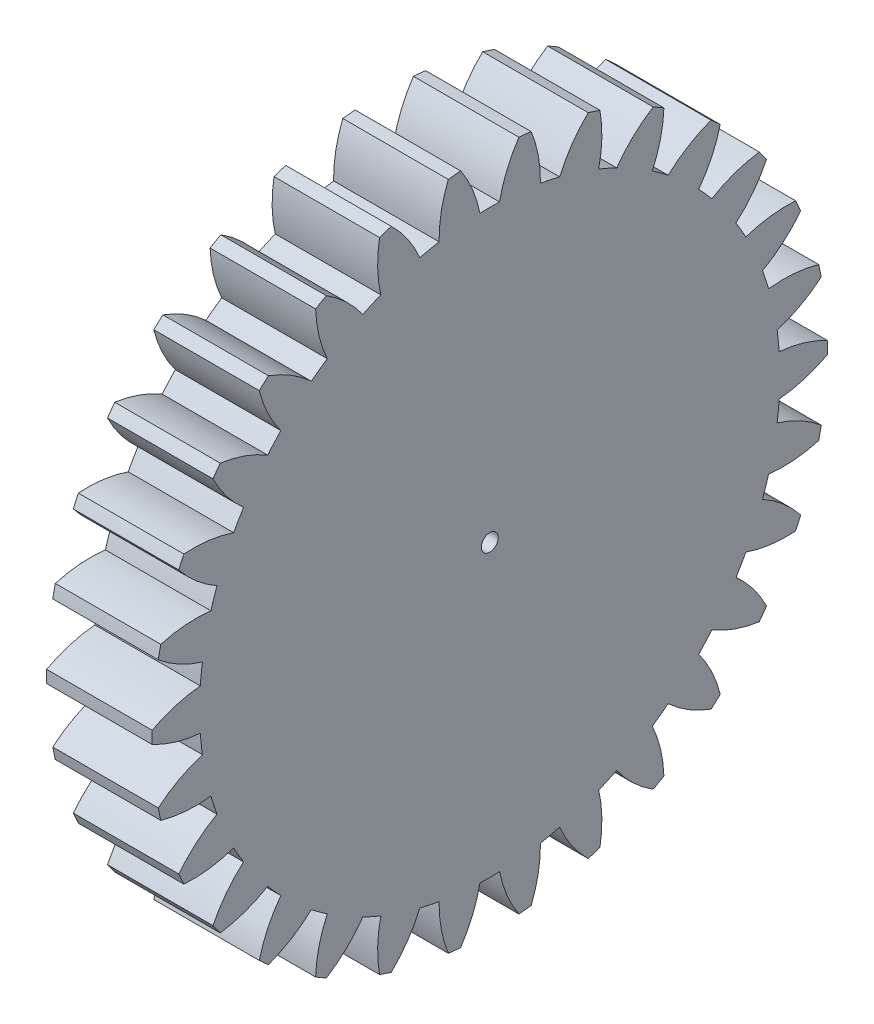
SolidWorks part; units mm, degrees
ref_plane "Plane1" through (0, 0, 0) normal (0, 0, 1) x (1, 0, 0)
ref_plane "Plane2" through (0, 0, 0) normal (0, 1, 0) x (1, 0, 0)
ref_plane "Plane3" through (0, 0, 0) normal (1, 0, 0) x (0, 0, -1)
other "Configuration Table"
sketch "HoldingSke" plane through (0, 0, 0) normal (0, 1, 0) x (1, 0, 0)
  line L0 (0, 0) -> (0.866, -0.5)
  line L1 (-15, 0) -> (100, 0) construction
  line L2 (0, 0) -> (-2.1039, 2.3779)
  line L3 (0, 0) -> (-11.863, 4.5341)
  line L4 (0, 0) -> (7.479, 4.318)
  line L5 (0, 0) -> (-46.8476, -17.4728)
  line L6 (0, 0) -> (-4.1448, -2.7965)
  line L7 (-2.1039, 2.3779) -> (8.6586, 51.2059)
  line L8 (-76.2, 54.61) -> (-76.1, 54.61)
  line L9 (-71.009, 38.7566) -> (-53.1078, 45.2721)
  line L10 (-76.2, 71.12) -> (104.1128, 71.12)
  line L11 (0, 0) -> (-5, 0)
  line L12 (-76.2, 101.6) -> (-76.162, 101.6)
  line L13 (24.9733, 27.94) -> (52.9518, 28.4284)
  line L14 (24.9733, 27.94) -> (24.9743, 27.94)
  line L15 (24.9733, 27.94) -> (100.4006, 29.5858)
  line L16 (-63.627, -1) -> (-12.827, -1)
  circle A0 centre (0, 0) radius 0.4
  circle A1 centre (0, 0) radius 13.749
  circle A2 centre (0, 0) radius 37.5
  circle A3 centre (0, 0) radius 0.4
  dimension "MHD" = 27.498
  dimension "Hub_dia" = 75
  dimension "Bore" = 0.8
  dimension "MBD" = 0.8
  dimension "Num_teeth" = 30
  dimension "Pitch" = 1
  dimension "Overall_len" = 50
  dimension "Show_teeth" = 30
  dimension "Thickness" = 5
  dimension "OAL" = 50.0001
  dimension "T_dim" = 0.1
  dimension "Ap" = 20
  dimension "H" = 19.05
  dimension "Pitch_radius" = 180.3128
  dimension "Width" = 5
  dimension "Backlash" = 0.038
  dimension "Addendum_fac" = 1
  dimension "Dedendum_fac" = 1.25
  dimension "Clearance_fac" = 0.25
  dimension "Dedendum_add" = 0.001
  dimension "Module" = 1
sketch "BasProSke" plane through (0, 0, 0) normal (0, 1, 0) x (1, 0, 0)
  line L0 (-10, 0) -> (60, 0) construction
  line L1 (0, 0) -> (0, 16)
  line L2 (0, 0) -> (5, 0)
  line L3 (5, 0) -> (5, 16)
  line L4 (5, 16) -> (0, 16)
  dimension "Thickness" = 5
  dimension "Diameter" = 32
revolve "Base-Revolve" add sketch "BasProSke" angle 360 about L0
sketch "TooCutSke" plane through (0, 0, 0) normal (1, 0, 0) x (0, 0, -1)
  line L1 (0, 0) -> (0, 107) construction
  line L2 (0, 0) -> (-0.8515, 14.9758) construction
  line L3 (0, 0) -> (-3.1323, 29.8014) construction
  line L4 (-0.8515, 14.9758) -> (-1.5661, 14.9007) construction
  arc A0 (0.4664, 13.7411) -> (-0.4664, 13.7411) centre (0, 0) ccw
  arc A1 (1.3975, 15.9644) -> (-1.3975, 15.9644) centre (0, 0) ccw
  circle A2 centre (0, 0) radius 15 construction
  circle A3 centre (0, 0) radius 14.0954 construction
  arc A4 (-0.4664, 13.7411) -> (-1.3975, 15.9644) centre (-6.3534, 12.5823) ccw
  arc A5 (1.3975, 15.9644) -> (0.4664, 13.7411) centre (6.3534, 12.5823) ccw
  dimension "Root_dia" = 27.498
  dimension "Overcut_dia" = 32.0508
  dimension "Pitch_dia" = 30
  dimension "Base_dia" = 28.1908
  dimension "Flank_rad" = 6
  dimension "Half_ang" = 6
  dimension "Half_CT" = 0.7185
extrude "ToothCut" cut sketch "TooCutSke" along normal through all
fillet "Breaks" [suppressed] radius 0.02
fillet "RootFillets" [suppressed] radius 0.251
pattern_circular "TeethCuts" count 30 every 12 about axis through (-10, 0, 0) along (1, 0, 0) of "ToothCut", "RootFillets", "Breaks"
sketch "HubNeaOneSke" plane through (0, 0, 0) normal (-1, 0, 0) x (0, 0, 1)
  circle A0 centre (0, 0) radius 13.749
  dimension "Diameter" = 27.498
extrude "HubNearOne" [suppressed] add sketch "HubNeaOneSke" along normal blind 45.0001
sketch "HubNeaBotSke" plane through (0, 0, 0) normal (-1, 0, 0) x (0, 0, 1)
  circle A0 centre (0, 0) radius 13.749
  dimension "Diameter" = 27.498
extrude "HubNearBoth" [suppressed] add sketch "HubNeaBotSke" along normal blind 22.5
ref_plane "FarPln" through (5, 0, 0) normal (1, 0, 0) x (0, 0, -1)
sketch "HubFarSke" plane through (5, 0, 0) normal (1, 0, 0) x (0, 0, -1)
  circle A0 centre (0, 0) radius 13.749
  dimension "Diameter" = 27.498
extrude "HubFar" [suppressed] add sketch "HubFarSke" along normal blind 22.5
sketch "BorSke" plane through (0, 0, 0) normal (1, 0, 0) x (0, 0, -1)
  circle A0 centre (0, 0) radius 0.4
  dimension "Diameter" = 0.8
extrude "Bore" cut sketch "BorSke" along normal mid plane 100.0001
sketch "KeySke" plane through (0, 0, 0) normal (1, 0, 0) x (0, 0, -1)
  line L0 (-0.05, 0) -> (-0.05, 0.5)
  line L1 (-0.05, 0.5) -> (0.05, 0.5)
  line L2 (0.05, 0.5) -> (0.05, 0)
  line L3 (0, 0) -> (0, 34) construction
  line L4 (-0.05, 0) -> (0.05, 0)
  dimension "Offset" = 0.5
  dimension "Width" = 0.1
extrude "Keyway" [suppressed] cut sketch "KeySke" along normal mid plane 100.0001
pattern_circular "Keyway2" [suppressed] count 2 every 90 about axis through (-10, 0, 0) along (1, 0, 0)
equation "' \"Module@HoldingSke\" = 6.35"
equation "' \"Num_teeth@HoldingSke\" = 12"
equation "' \"Ap@HoldingSke\" =  20"
equation "' \"Ap@HoldingSke\" = 20"
equation "' \"Width@HoldingSke\" = 0.5 * 25.4"
equation "' \"Hub_dia@HoldingSke\"= 1 * 25.4"
equation "' \"Hub_dia@HoldingSke\" = 1 * 25.4"
equation "' \"Overall_len@HoldingSke\" = 1.0 * 25.4"
equation "' \"Bore@HoldingSke\" = 0.75 * 25.4"
equation "' \"T_dim@HoldingSke\" = 0.1 * 25.4"
equation "' \"Width@KeySke\" = 0.25 * 25.4"
equation "' \"Show_teeth@HoldingSke\" = 13"
equation "' \"Backlash@HoldingSke\" = 0.009 * 25.4"
equation "' \"Addendum_fac@HoldingSke\" = 1.0"
equation "' \"Dedendum_fac@HoldingSke\" = 1.25"
equation "' \"Dedendum_add@HoldingSke\" = 0.00005 * 25.4"
equation "' \"Clearance_fac@HoldingSke\" = 0.25"
equation "\"Pitch@HoldingSke\" = 1 / \"Module@HoldingSke\""
equation "\"Overcut_dia@TooCutSke\" = (\"Num_teeth@HoldingSke\" + 2 * \"Addendum_fac@HoldingSke\") / \"Pitch@HoldingSke\" + 0.002 * 25.4"
equation "\"Pitch_dia@TooCutSke\" = \"Num_teeth@HoldingSke\" / \"Pitch@HoldingSke\""
equation "\"Base_dia@TooCutSke\" = \"Num_teeth@HoldingSke\" / \"Pitch@HoldingSke\" * cos((\"Ap@HoldingSke\"  * 3.14159265 / 180))"
equation "\"Root_dia@TooCutSke\" = (\"Num_teeth@HoldingSke\" + 2) / \"Pitch@HoldingSke\" - 2 * (\"Addendum_fac@HoldingSke\" + \"Dedendum_fac@HoldingSke\") / \"Pitch@HoldingSke\" - \"Dedendum_add@HoldingSke\" * 2"
equation "\"Half_ang@TooCutSke\" = 180 / \"Num_teeth@HoldingSke\""
equation "\"Half_CT@TooCutSke\" = \"Num_teeth@HoldingSke\" / \"Pitch@HoldingSke\" * sin((3.14159265 / 2 / \"Num_teeth@HoldingSke\")) / 2 - 7 * \"Backlash@HoldingSke\" / 4"
equation "\"Flank_rad@TooCutSke\" = \"Num_teeth@HoldingSke\" / \"Pitch@HoldingSke\" / 5"
equation "\"Radius@RootFillets\" = \"Clearance_fac@HoldingSke\" / \"Pitch@HoldingSke\" + \"Dedendum_add@HoldingSke\""
equation "\"Break_rad@Breaks\" = 0.02 / \"Pitch@HoldingSke\""
equation "\"Thickness@HoldingSke\" = \"Width@HoldingSke\""
equation "\"OAL@HoldingSke\" = \"Thickness@HoldingSke\""
equation "\"MHD@HoldingSke\" = (\"Num_teeth@HoldingSke\" + 2) / \"Pitch@HoldingSke\" - 2 * (\"Addendum_fac@HoldingSke\" + \"Dedendum_fac@HoldingSke\")  / \"Pitch@HoldingSke\" - \"Dedendum_add@HoldingSke\" * 2"
equation "\"MBD@HoldingSke\" = (\"Num_teeth@HoldingSke\" + 2) / \"Pitch@HoldingSke\" - 2 * (\"Addendum_fac@HoldingSke\" + \"Dedendum_fac@HoldingSke\")  / \"Pitch@HoldingSke\" - \"Dedendum_add@HoldingSke\" * 2 - 0.002 * 25.4"
equation "\"MHD@HoldingSke\" = ((sgn( \"MHD@HoldingSke\" - \"Hub_dia@HoldingSke\" )-1)*( \"MHD@HoldingSke\" - \"Hub_dia@HoldingSke\" ))/-2+ \"Hub_dia@HoldingSke\""
equation "\"MBD@HoldingSke\" = ((sgn( \"MBD@HoldingSke\" - \"Bore@HoldingSke\" )-1)*( \"MBD@HoldingSke\" - \"Bore@HoldingSke\" ))/-2+ \"Bore@HoldingSke\""
equation "\"OAL@HoldingSke\" = ((sgn( \"OAL@HoldingSke\" - \"Overall_len@HoldingSke\" )+1)*( \"OAL@HoldingSke\" - \"Overall_len@HoldingSke\" ))/2 + \"Overall_len@HoldingSke\" + 0.000002 * 25.4"
equation "\"Num_teeth@TeethCuts\" = int( \"Show_teeth@HoldingSke\" ) + 1"
equation "\"Num_teeth@TeethCuts\" = ((sgn( \"Num_teeth@TeethCuts\" - \"Num_teeth@HoldingSke\" )-1)*( \"Num_teeth@TeethCuts\" - \"Num_teeth@HoldingSke\" ))/-2+ \"Num_teeth@HoldingSke\""
equation "\"Num_teeth@TeethCuts\" = ((sgn( \"Num_teeth@TeethCuts\" - 2.0)+1)*( \"Num_teeth@TeethCuts\" - 2.0))/2 +2.0"
equation "\"Angle@TeethCuts\" = 360.0 / \"Num_teeth@HoldingSke\""
equation "\"Diameter@BasProSke\" = (\"Num_teeth@HoldingSke\" + 2 * \"Addendum_fac@HoldingSke\") / \"Pitch@HoldingSke\""
equation "\"Thickness@BasProSke\"  = \"Thickness@HoldingSke\""
equation "' \"Fillet_rad@BasProSke\" =  \"Thickness@HoldingSke\" * 0.05"
equation "' \"Fillet_rad@BasProSke\" = \"Thickness@HoldingSke\" * 0.05"
equation "\"MHD@HoldingSke\" = ((sgn( \"MHD@HoldingSke\" - \"Root_dia@TooCutSke\" )-1)*( \"MHD@HoldingSke\" - \"Root_dia@TooCutSke\" ))/-2+ \"Root_dia@TooCutSke\""
equation "\"Diameter@HubNeaOneSke\" = \"MHD@HoldingSke\""
equation "\"Length@HubNearOne\" = \"OAL@HoldingSke\" - \"Thickness@BasProSke\""
equation "\"Diameter@HubNeaBotSke\" = \"MHD@HoldingSke\""
equation "\"Length@HubNearBoth\" = ( \"OAL@HoldingSke\" - \"Thickness@BasProSke\" ) / 2.0"
equation "\"Thickness@FarPln\" = \"Thickness@BasProSke\""
equation "\"Diameter@HubFarSke\" = \"MHD@HoldingSke\""
equation "\"Length@HubFar\" = ( \"OAL@HoldingSke\" - \"Thickness@BasProSke\" ) / 2.0"
equation "\"Diameter@BorSke\" = \"MBD@HoldingSke\""
equation "\"D1@Bore\" = \"OAL@HoldingSke\" * 2.0"
equation "\"D1@Keyway\" = \"OAL@HoldingSke\" * 2.0"
equation "\"Offset@KeySke\" = \"T_dim@HoldingSke\" + \"MBD@HoldingSke\" / 2.0"
